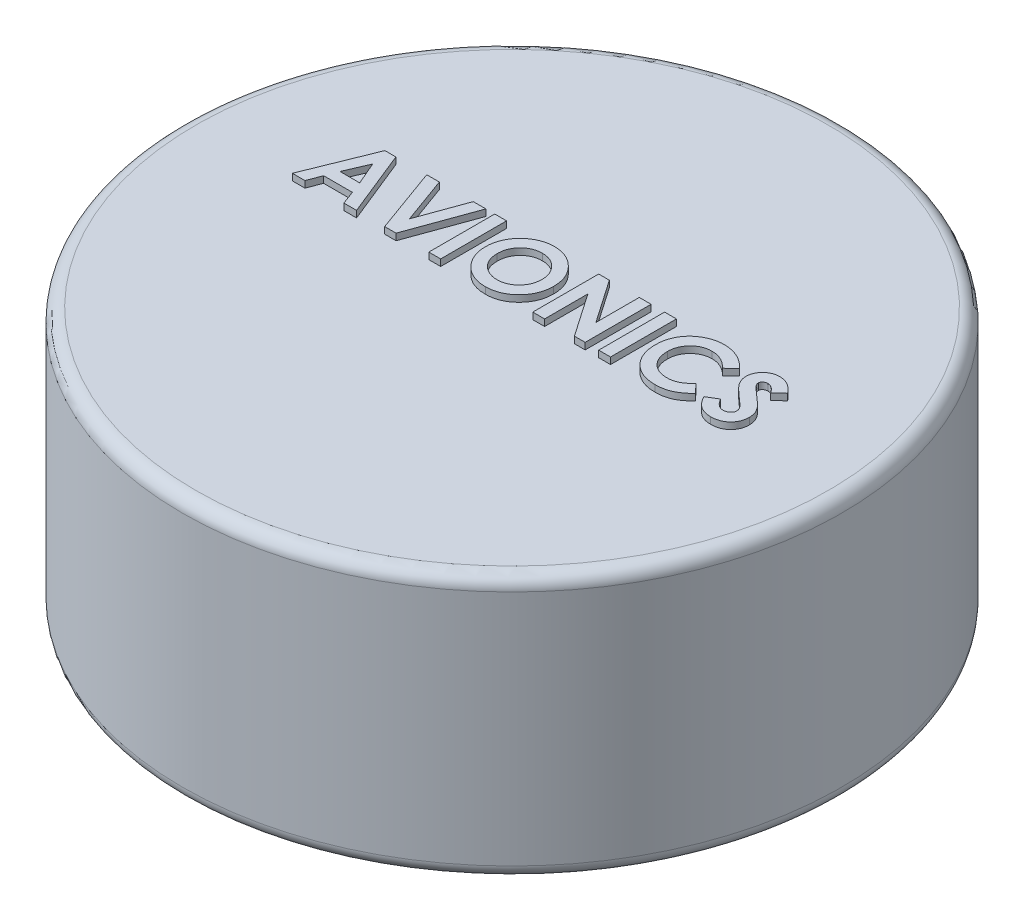
SolidWorks part; units mm, degrees
ref_plane "Front Plane" through (0, 0, 0) normal (0, 0, 1) x (1, 0, 0)
ref_plane "Top Plane" through (0, 0, 0) normal (0, 1, 0) x (1, 0, 0)
ref_plane "Right Plane" through (0, 0, 0) normal (1, 0, 0) x (0, 0, -1)
sketch "Sketch1" plane through (0, 0, 0) normal (0, 1, 0) x (1, 0, 0)
  circle A0 centre (0, 0) radius 63.5
  dimension "D1" = 127
extrude "Boss-Extrude1" add sketch "Sketch1" along normal blind 50.8
sketch "Sketch2" plane through (0, 50.8, 0) normal (0, 1, 0) x (1, 0, 0)
  line L0 (63.5, 0) -> (-63.5, 0) construction
  text T0 "<b>AVIONICS</b>" font "Century Gothic" height 12.7
  point P5 (0, 0)
  dimension "D1" = 127
extrude "Boss-Extrude2" add sketch "Sketch2" along normal blind 1.27
fillet "Fillet1" radius 2.54 2 edges at (0, 0, 63.5) (0, 50.8, 63.5)
sketch "Sketch3" plane through (0, 0, 0) normal (0, 0, 1) x (1, 0, 0)
  line L0 (0, 0) -> (0, 50.8) construction
  line L1 (1.7096, 50.8) -> (-4.8414, 50.8) construction
  text T0 "<b>AVIONICS</b>" font "Century Gothic" height 6.35
extrude "Cut-Extrude2" cut sketch "Sketch3" against normal mid plane 1.27
